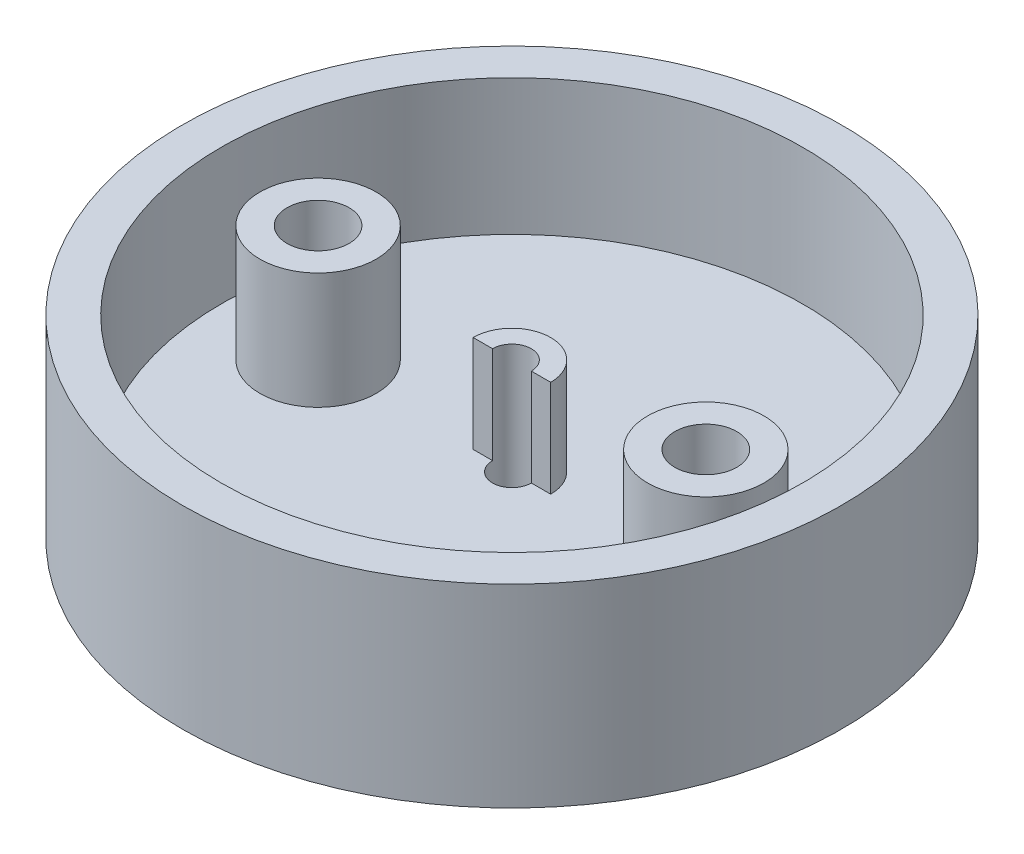
SolidWorks part; units mm, degrees
ref_plane "Alzado" through (0, 0, 0) normal (0, 0, 1) x (1, 0, 0)
ref_plane "Planta" through (0, 0, 0) normal (0, 1, 0) x (1, 0, 0)
ref_plane "Vista lateral" through (0, 0, 0) normal (1, 0, 0) x (0, 0, -1)
sketch "Croquis1" plane through (0, 0, 0) normal (0, 1, 0) x (1, 0, 0)
  line L1 (-10, 0) -> (0, 0) construction
  line L2 (0, 0) -> (10, 0) construction
  circle A0 centre (0, 0) radius 17
  circle A2 centre (0, 0) radius 1
  circle A3 centre (-10, 0) radius 1.6
  circle A4 centre (10, 0) radius 1.6
  dimension "D1" = 34
  dimension "D3" = 2
  dimension "D4" = 3.2
  dimension "D5" = 10
extrude "Saliente-Extruir1" add sketch "Croquis1" along normal blind 3
sketch "Croquis2" plane through (0, 3, 0) normal (0, 1, 0) x (1, 0, 0)
  circle A0 centre (0, 0) radius 15
  circle A1 centre (0, 0) radius 17 construction
  circle A2 centre (0, 0) radius 17
  dimension "D1" = 30
extrude "Saliente-Extruir2" add sketch "Croquis2" along normal blind 7
sketch "Croquis3" plane through (0, 3, 0) normal (0, 1, 0) x (1, 0, 0)
  circle A0 centre (10, 0) radius 3
  circle A1 centre (-10, 0) radius 3
  circle A2 centre (-10, 0) radius 1.6 construction
  circle A3 centre (10, 0) radius 1.6 construction
  circle A4 centre (-10, 0) radius 1.6
  circle A5 centre (10, 0) radius 1.6
  dimension "D1" = 6
extrude "Saliente-Extruir3" add sketch "Croquis3" along normal blind 6
sketch "Croquis4" plane through (0, 3, 0) normal (0, 1, 0) x (1, 0, 0)
  line L0 (1, 0) -> (2, 0)
  line L1 (-1, 0) -> (-2, 0)
  arc A0 (2, 0) -> (-2, 0) centre (0, 0) ccw
  circle A1 centre (0, 0) radius 1 construction
  arc A2 (1, 0) -> (-1, 0) centre (0, 0) ccw
  dimension "D1" = 4
extrude "Saliente-Extruir4" add sketch "Croquis4" along normal blind 5
